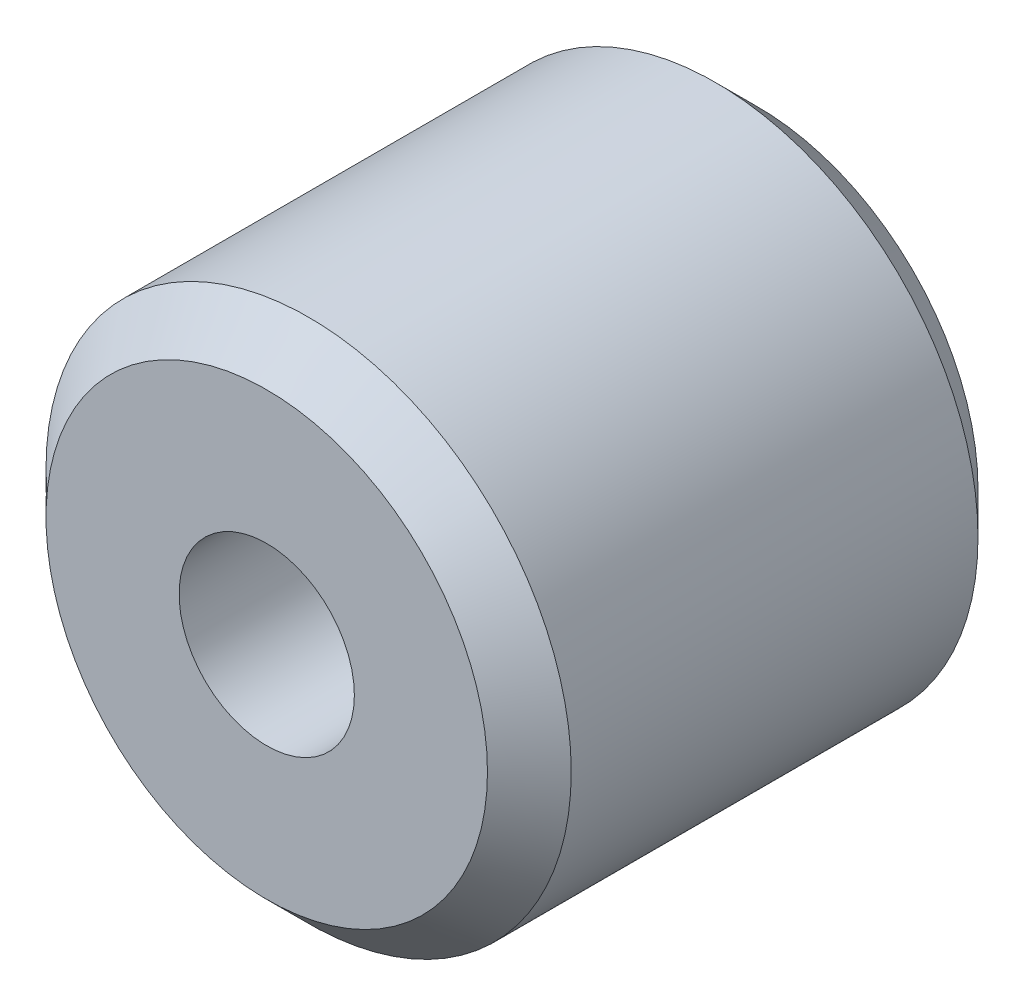
SolidWorks part; units mm, degrees
ref_plane "Front Plane" through (0, 0, 0) normal (0, 0, 1) x (1, 0, 0)
ref_plane "Top Plane" through (0, 0, 0) normal (0, 1, 0) x (1, 0, 0)
ref_plane "Right Plane" through (0, 0, 0) normal (1, 0, 0) x (0, 0, -1)
sketch "Sketch1" plane through (0, 0, 0) normal (0, 0, 1) x (1, 0, 0)
  circle A0 centre (0, 0) radius 4.765
  circle A1 centre (0, 0) radius 1.59
  dimension "D1" = 9.53
  dimension "D2" = 3.18
extrude "Boss-Extrude1" add sketch "Sketch1" along normal mid plane 8.9
chamfer "Chamfer1" distance 0.76 2 edges at (4.765, 0, -4.45) (4.765, 0, 4.45)
